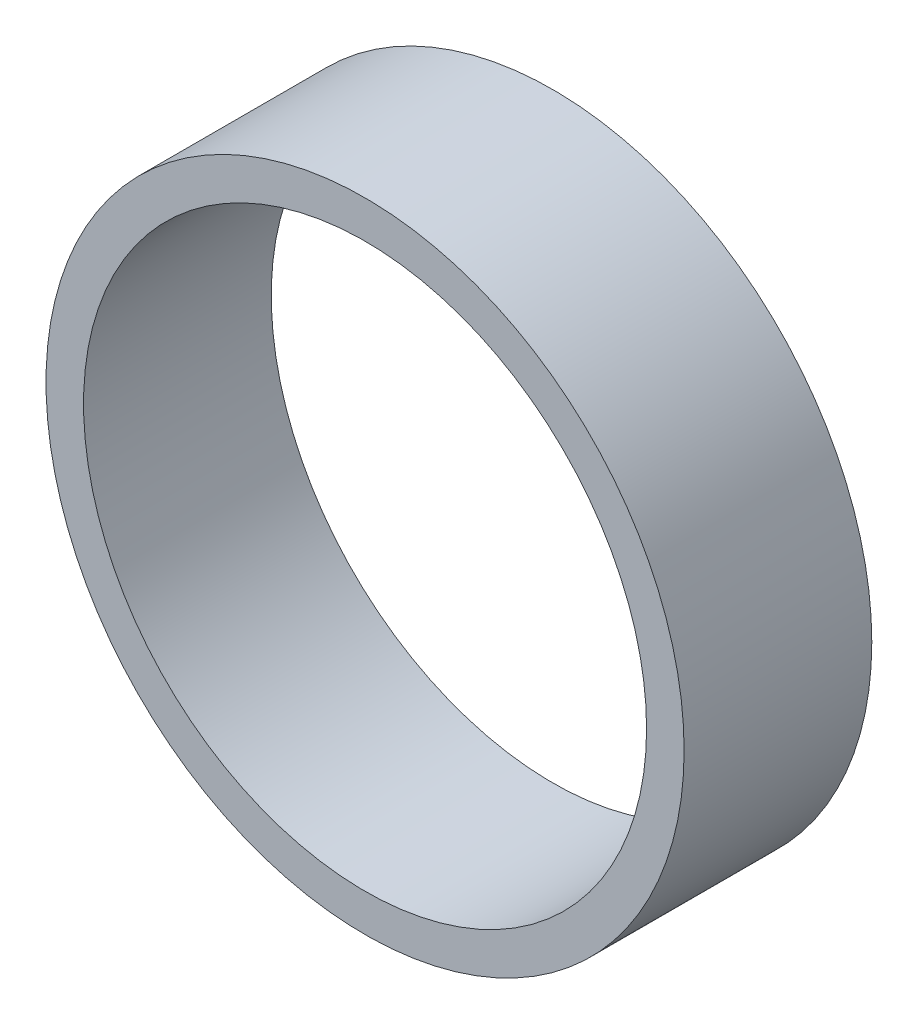
SolidWorks part; units mm, degrees
ref_plane "Front Plane" through (0, 0, 0) normal (0, 0, 1) x (1, 0, 0)
ref_plane "Top Plane" through (0, 0, 0) normal (0, 1, 0) x (1, 0, 0)
ref_plane "Right Plane" through (0, 0, 0) normal (1, 0, 0) x (0, 0, -1)
sketch "Sketch1" plane through (0, 0, 0) normal (0, 0, 1) x (1, 0, 0)
  circle A0 centre (0, 0) radius 15
  circle A1 centre (0, 0) radius 17
extrude "Boss-Extrude1" add sketch "Sketch1" along normal blind 10
